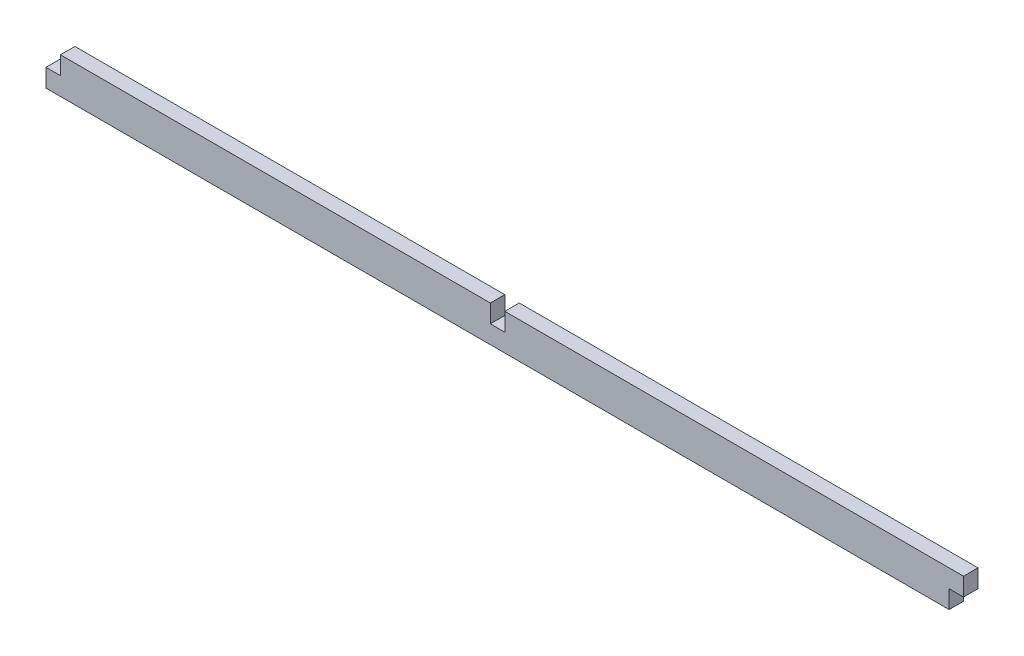
SolidWorks part; units mm, degrees
ref_plane "Front Plane" through (0, 0, 0) normal (0, 0, 1) x (1, 0, 0)
ref_plane "Top Plane" through (0, 0, 0) normal (0, 1, 0) x (1, 0, 0)
ref_plane "Right Plane" through (0, 0, 0) normal (1, 0, 0) x (0, 0, -1)
sketch "Sketch1" plane through (0, 0, 0) normal (0, 0, 1) x (1, 0, 0)
  line L5 (-5, 0) -> (5, 0)
  line L6 (-312.5, 12.5) -> (-5, 12.5)
  line L15 (-312.5, 12.5) -> (-312.5, -12.5)
  line L16 (-312.5, -12.5) -> (312.5, -12.5)
  line L17 (312.5, 0) -> (312.5, -12.5)
  line L18 (-312.5, 12.5) -> (312.5, -12.5) construction
  line L19 (-312.5, -12.5) -> (312.5, 12.5) construction
  line L20 (5, 0) -> (5, 12.5)
  line L21 (-5, 0) -> (-5, 12.5)
  line L22 (5, 12.5) -> (312.5, 12.5)
  line L23 (312.5, 0) -> (322.5, 0)
  line L24 (322.5, 0) -> (322.5, 12.5)
  line L25 (322.5, 12.5) -> (312.5, 12.5)
  line L26 (-312.5, 0) -> (-302.5, 0)
  line L27 (-302.5, 0) -> (-302.5, 12.5)
  point P0 (0, 0)
  point P9 (0, 0)
  dimension "D1" = 625
  dimension "D2" = 25
  dimension "D3" = 10
  dimension "D4" = 10
  dimension "D5" = 10
extrude "Boss-Extrude1" add sketch "Sketch1" along normal blind 10 contours L27 L26 L15 L16 L17 L23 L24 L25 L22 L20 L5 L21 L6
